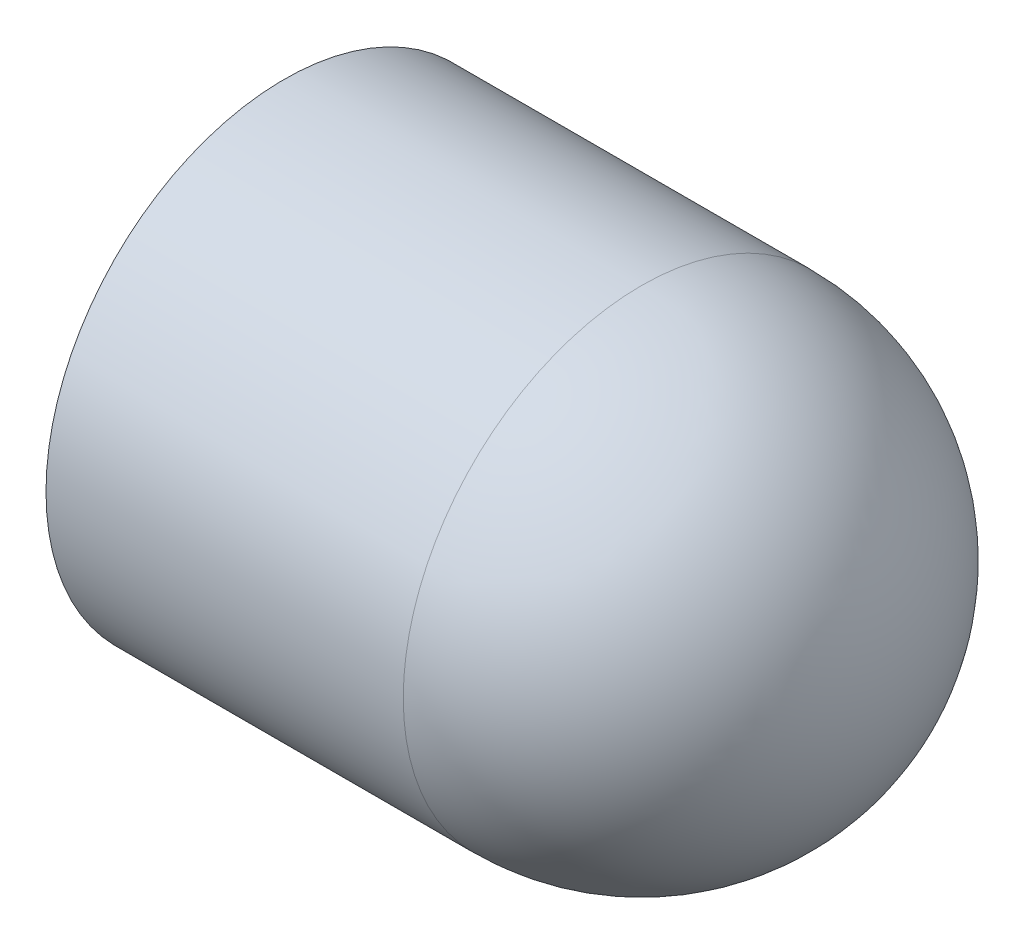
SolidWorks part; units mm, degrees
ref_plane "Спереди" through (0, 0, 0) normal (0, 0, 1) x (1, 0, 0)
ref_plane "Сверху" through (0, 0, 0) normal (0, 1, 0) x (1, 0, 0)
ref_plane "Справа" through (0, 0, 0) normal (1, 0, 0) x (0, 0, -1)
sketch "Эскиз1" plane through (0, 0, 0) normal (0, 0, 1) x (1, 0, 0)
  line L0 (4.3589, 10) -> (19.3589, 10)
  line L2 (0, 0) -> (64.4857, 0) construction
  line L3 (4.3589, 10) -> (4.3589, 9)
  line L5 (10, 0) -> (29.3589, 0)
  line L6 (10, 7.5) -> (10, 7.5)
  line L7 (10, 7.5) -> (19.3589, 7.5)
  arc A0 (10, 0) -> (4.3589, 9) centre (0, 0) ccw
  arc A1 (19.3589, 10) -> (29.3589, 0) centre (19.3589, 0) cw
  arc A2 (12.5, 0) -> (10, 7.5) centre (0, 0) ccw
  arc A3 (19.3589, 7.5) -> (26.8589, 0) centre (19.3589, 0) cw
  dimension "D1" = 20
  dimension "D2" = 1
  dimension "D3" = 15
  dimension "D4" = 2.5
revolve "Повернуть1" add sketch "Эскиз1" angle 360 about L5
